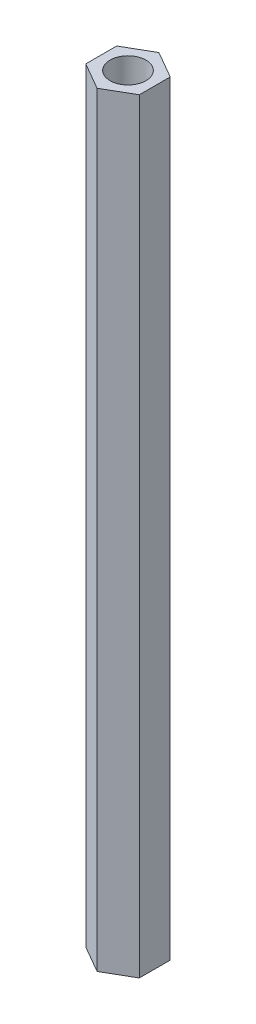
SolidWorks part; units mm, degrees
ref_plane "Front Plane" through (0, 0, 0) normal (0, 0, 1) x (1, 0, 0)
ref_plane "Top Plane" through (0, 0, 0) normal (0, 1, 0) x (1, 0, 0)
ref_plane "Right Plane" through (0, 0, 0) normal (1, 0, 0) x (0, 0, -1)
sketch "Sketch1" plane through (0, 0, 0) normal (0, 1, 0) x (1, 0, 0)
  line L1 (0, -2.0531) -> (1.778, -1.0265)
  line L2 (1.778, -1.0265) -> (1.778, 1.0265)
  line L3 (1.778, 1.0265) -> (0, 2.0531)
  line L4 (0, 2.0531) -> (-1.778, 1.0265)
  line L5 (-1.778, 1.0265) -> (-1.778, -1.0265)
  line L6 (-1.778, -1.0265) -> (0, -2.0531)
  circle A0 centre (0, 0) radius 1.778 construction
  circle A1 centre (0, 0) radius 1.1906
  dimension "D1" = 2.3813
  dimension "D2" = 1.778
extrude "Boss-Extrude1" add sketch "Sketch1" along normal blind 50.8
